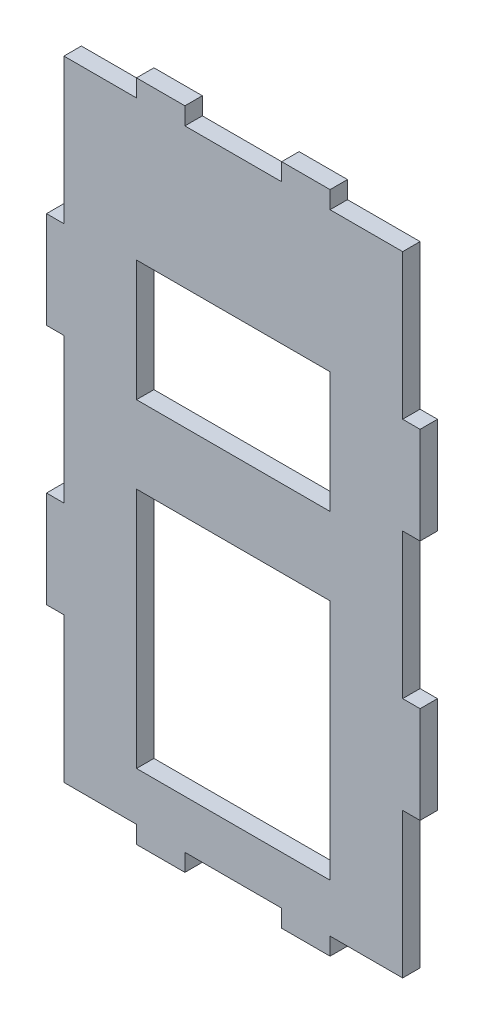
SolidWorks part; units mm, degrees
ref_plane "Front Plane" through (0, 0, 0) normal (0, 0, 1) x (1, 0, 0)
ref_plane "Top Plane" through (0, 0, 0) normal (0, 1, 0) x (1, 0, 0)
ref_plane "Right Plane" through (0, 0, 0) normal (1, 0, 0) x (0, 0, -1)
sketch "Sketch1" plane through (0, 0, 0) normal (0, 0, 1) x (1, 0, 0)
  line L1 (0, 0) -> (98.044, 0)
  line L2 (0, 0) -> (0, 174.244)
  line L3 (0, 174.244) -> (98.044, 174.244)
  line L4 (98.044, 0) -> (98.044, 174.244)
  dimension "D1" = 98.044
  dimension "D2" = 174.244
extrude "Boss-Extrude1" add sketch "Sketch1" along normal blind 4.572
sketch "Sketch2" plane through (0, 0, 4.572) normal (0, 0, 1) x (1, 0, 0)
  line L0 (0, 0) -> (98.044, 0) construction
  line L1 (0, 0) -> (23.622, 0)
  line L2 (0, 0) -> (0, 4.572)
  line L3 (0, 4.572) -> (23.622, 4.572)
  line L4 (23.622, 0) -> (23.622, 4.572)
  line L5 (36.322, 0) -> (61.722, 0)
  line L6 (36.322, 0) -> (36.322, 4.572)
  line L7 (36.322, 4.572) -> (61.722, 4.572)
  line L8 (61.722, 0) -> (61.722, 4.572)
  line L9 (98.044, 174.244) -> (0, 174.244) construction
  line L10 (98.044, 0) -> (74.422, 0)
  line L11 (98.044, 0) -> (98.044, 4.572)
  line L12 (98.044, 4.572) -> (74.422, 4.572)
  line L13 (74.422, 0) -> (74.422, 4.572)
  line L14 (0, 174.244) -> (23.622, 174.244)
  line L15 (0, 174.244) -> (0, 169.672)
  line L16 (0, 169.672) -> (23.622, 169.672)
  line L17 (23.622, 174.244) -> (23.622, 169.672)
  line L18 (36.322, 174.244) -> (61.722, 174.244)
  line L19 (36.322, 174.244) -> (36.322, 169.672)
  line L20 (36.322, 169.672) -> (61.722, 169.672)
  line L21 (61.722, 174.244) -> (61.722, 169.672)
  line L23 (98.044, 174.244) -> (74.422, 174.244)
  line L24 (98.044, 174.244) -> (98.044, 169.672)
  line L25 (98.044, 169.672) -> (74.422, 169.672)
  line L26 (74.422, 174.244) -> (74.422, 169.672)
  dimension "D1" = 4.572
  dimension "D2" = 4.572
  dimension "D3" = 4.572
  dimension "D4" = 12.7
  dimension "D5" = 23.622
  dimension "D6" = 23.622
  dimension "D7" = 25.4
  dimension "D8" = 4.572
  dimension "D9" = 4.572
  dimension "D10" = 4.572
  dimension "D11" = 25.4
  dimension "D12" = 12.7
  dimension "D13" = 23.622
  dimension "D14" = 23.622
extrude "Cut-Extrude1" cut sketch "Sketch2" against normal blind 4.572
sketch "Sketch3" plane through (0, 0, 4.572) normal (0, 0, 1) x (1, 0, 0)
  line L0 (0, 169.672) -> (0, 4.572) construction
  line L1 (0, 4.572) -> (4.572, 4.572)
  line L2 (0, 4.572) -> (0, 42.672)
  line L3 (0, 42.672) -> (4.572, 42.672)
  line L4 (4.572, 4.572) -> (4.572, 42.672)
  line L5 (98.044, 4.572) -> (93.472, 4.572)
  line L6 (98.044, 4.572) -> (98.044, 42.672)
  line L7 (98.044, 42.672) -> (93.472, 42.672)
  line L8 (93.472, 4.572) -> (93.472, 42.672)
  line L9 (0, 106.172) -> (4.572, 106.172)
  line L10 (0, 106.172) -> (0, 68.072)
  line L11 (0, 68.072) -> (4.572, 68.072)
  line L12 (4.572, 106.172) -> (4.572, 68.072)
  line L13 (98.044, 4.572) -> (98.044, 169.672) construction
  line L14 (0, 169.672) -> (4.572, 169.672)
  line L15 (0, 169.672) -> (0, 131.572)
  line L16 (0, 131.572) -> (4.572, 131.572)
  line L17 (4.572, 169.672) -> (4.572, 131.572)
  line L18 (98.044, 169.672) -> (93.472, 169.672)
  line L19 (98.044, 169.672) -> (98.044, 131.572)
  line L20 (98.044, 131.572) -> (93.472, 131.572)
  line L21 (93.472, 169.672) -> (93.472, 131.572)
  line L22 (98.044, 106.172) -> (93.472, 106.172)
  line L23 (98.044, 106.172) -> (98.044, 68.072)
  line L24 (98.044, 68.072) -> (93.472, 68.072)
  line L25 (93.472, 106.172) -> (93.472, 68.072)
  point P32 (2.286, 42.672)
  dimension "D1" = 38.1
  dimension "D2" = 38.1
  dimension "D3" = 38.1
  dimension "D4" = 38.1
  dimension "D5" = 38.1
  dimension "D6" = 38.1
  dimension "D7" = 25.4
  dimension "D8" = 25.4
  dimension "D9" = 4.572
  dimension "D10" = 4.572
  dimension "D11" = 4.572
  dimension "D12" = 4.572
  dimension "D13" = 4.572
  dimension "D14" = 4.572
extrude "Cut-Extrude2" cut sketch "Sketch3" against normal blind 4.572
sketch "Sketch4" plane through (0, 0, 4.572) normal (0, 0, 1) x (1, 0, 0)
  line L0 (23.622, 4.572) -> (4.572, 4.572) construction
  line L1 (23.622, 80.772) -> (74.422, 80.772)
  line L2 (23.622, 80.772) -> (23.622, 17.272)
  line L3 (23.622, 17.272) -> (74.422, 17.272)
  line L4 (74.422, 80.772) -> (74.422, 17.272)
  line L5 (23.622, 132.842) -> (74.422, 132.842)
  line L6 (23.622, 132.842) -> (23.622, 101.092)
  line L7 (23.622, 101.092) -> (74.422, 101.092)
  line L8 (74.422, 132.842) -> (74.422, 101.092)
  line L9 (4.572, 4.572) -> (4.572, 42.672) construction
  line L10 (4.572, 131.572) -> (4.572, 169.672) construction
  dimension "D1" = 63.5
  dimension "D2" = 12.7
  dimension "D3" = 20.32
  dimension "D4" = 31.75
  dimension "D5" = 50.8
  dimension "D6" = 50.8
  dimension "D7" = 19.05
  dimension "1.25in" = 19.05
extrude "Cut-Extrude3" cut sketch "Sketch4" against normal blind 4.572
